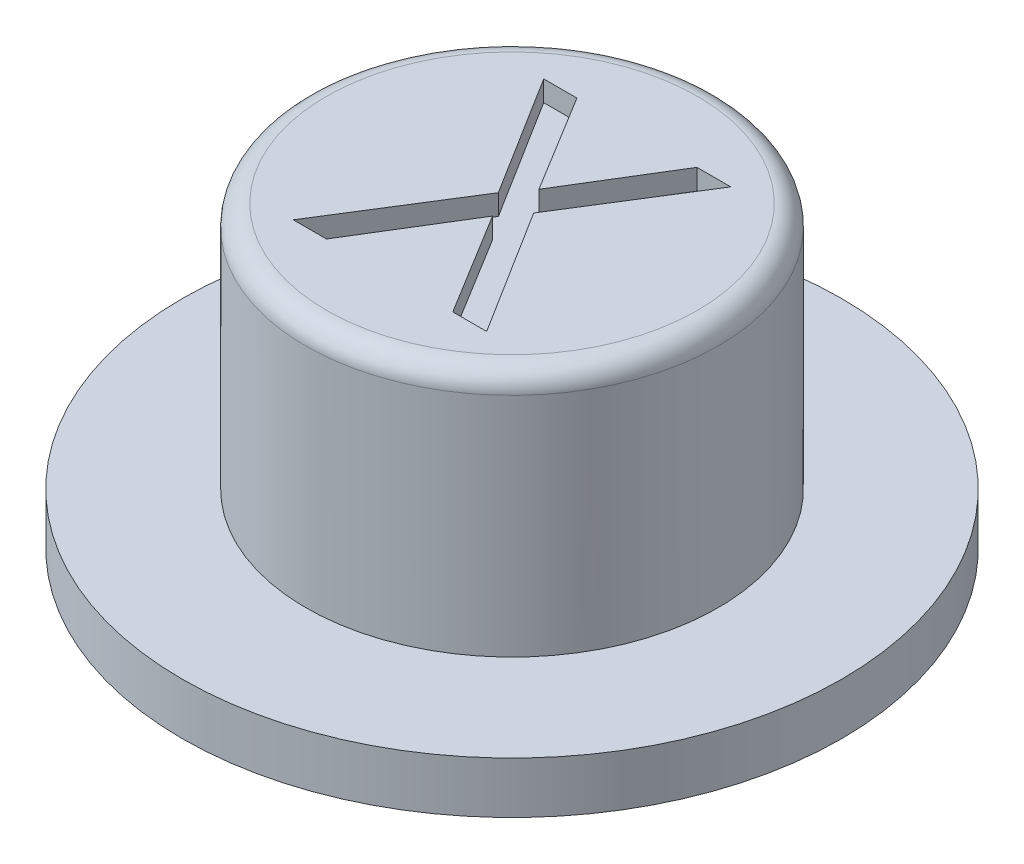
SolidWorks part; units mm, degrees
ref_plane "Front Plane" through (0, 0, 0) normal (0, 0, 1) x (1, 0, 0)
ref_plane "Top Plane" through (0, 0, 0) normal (0, 1, 0) x (1, 0, 0)
ref_plane "Right Plane" through (0, 0, 0) normal (1, 0, 0) x (0, 0, -1)
sketch "Sketch1" plane through (0, 0, 0) normal (0, 0, 1) x (1, 0, 0)
  line L1 (0, 7.25) -> (5, 7.25)
  line L2 (5, 7.25) -> (5, 1.25)
  line L3 (5, 1.25) -> (8, 1.25)
  line L4 (8, 1.25) -> (8, 0)
  line L6 (0, 7.25) -> (0, 6.9292) construction
  line L7 (0, 7.25) -> (0, 0)
  line L10 (0, 0) -> (8, 0)
  dimension "D1" = 5
  dimension "D2" = 3
  dimension "D3" = 6
  dimension "D4" = 1.25
revolve "Revolve1" add sketch "Sketch1" angle 360 about L6
sketch "Sketch2" plane through (0, 0, 0) normal (0, -1, 0) x (1, 0, 0)
  line L1 (-1.25, -1.75) -> (1.25, -1.75)
  line L2 (-1.25, -1.75) -> (-1.25, 1.75)
  line L3 (-1.25, 1.75) -> (1.25, 1.75)
  line L4 (1.25, -1.75) -> (1.25, 1.75)
  line L5 (-1.25, -1.75) -> (1.25, 1.75) construction
  line L6 (-1.25, 1.75) -> (1.25, -1.75) construction
  point P0 (0, 0)
  dimension "D1" = 2.5
  dimension "D2" = 3.5
extrude "Cut-Extrude1" cut sketch "Sketch2" against normal blind 3.5 contours L3 L4 L1 L2
fillet "Fillet1" radius 0.5 1 edges at (-5, 7.25, 0)
sketch "Sketch3" plane through (0, 7.25, 0) normal (0, 1, 0) x (1, 0, 0)
  line L0 (-3.3541, -3) -> (3.3541, -3) construction
  line L1 (0, 0) -> (0, -3) construction
  circle A0 centre (0, 0) radius 4.5 construction
  text T0 "X" font "Century Gothic" height 6
  dimension "D1" = 3
extrude "Cut-Extrude2" cut sketch "Sketch3" against normal blind 0.5
